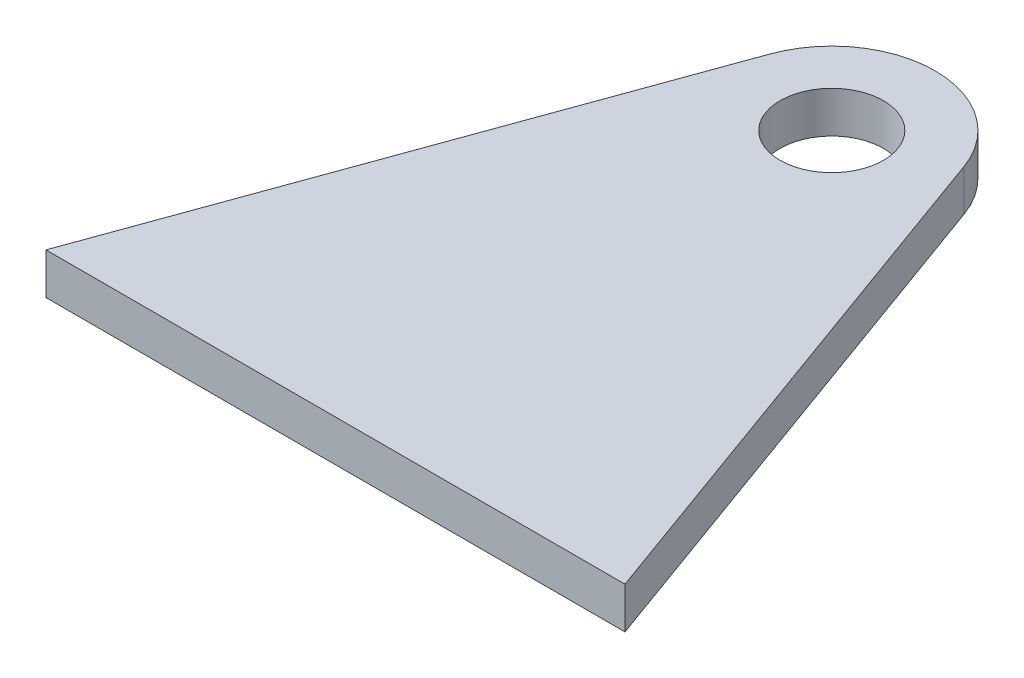
SolidWorks part; units mm, degrees
ref_plane "Front Plane" through (0, 0, 0) normal (0, 0, 1) x (1, 0, 0)
ref_plane "Top Plane" through (0, 0, 0) normal (0, 1, 0) x (1, 0, 0)
ref_plane "Right Plane" through (0, 0, 0) normal (1, 0, 0) x (0, 0, -1)
sketch "Sketch1" plane through (0, 0, 0) normal (0, 1, 0) x (1, 0, 0)
  line L0 (0, 0) -> (280, 0)
  line L1 (140, 0) -> (140, 240) construction
  line L2 (92.9824, 257.0102) -> (0, 0)
  line L3 (187.0176, 257.0102) -> (280, 0)
  circle A0 centre (140, 240) radius 25
  arc A1 (92.9824, 257.0102) -> (187.0176, 257.0102) centre (140, 240) cw
  dimension "D3" = 50
  dimension "D4" = 50
  dimension "D1" = 280
  dimension "D2" = 240
extrude "Boss-Extrude1" add sketch "Sketch1" along normal blind 20
